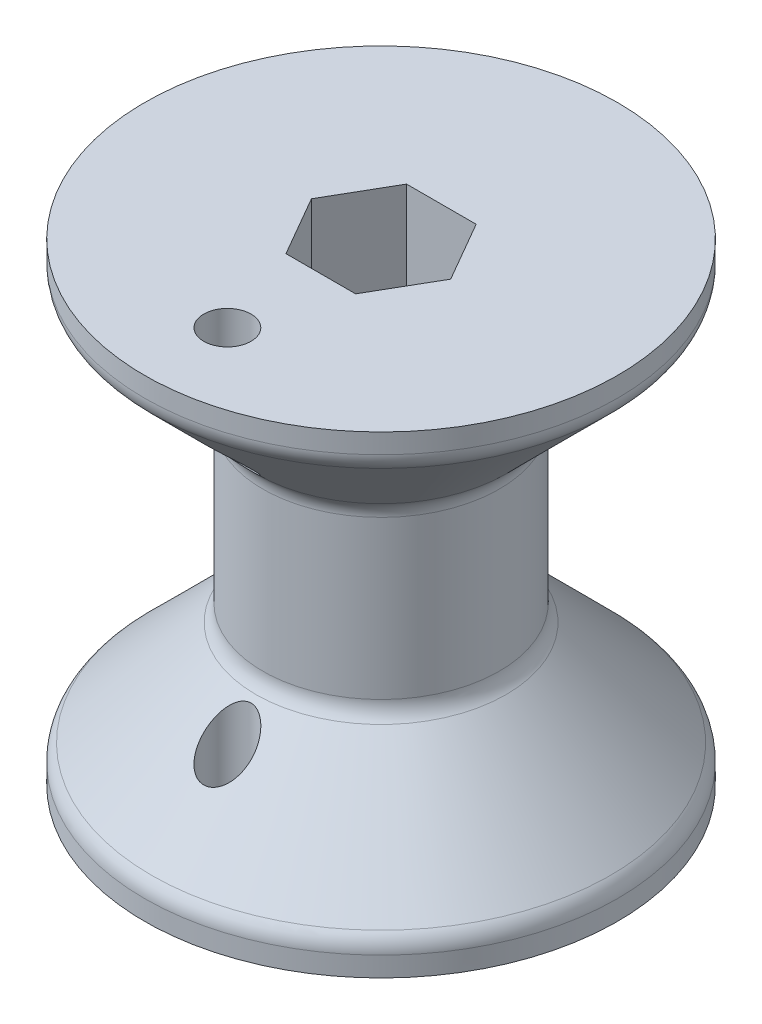
SolidWorks part; units mm, degrees
ref_plane "Front Plane" through (0, 0, 0) normal (0, 0, 1) x (1, 0, 0)
ref_plane "Top Plane" through (0, 0, 0) normal (0, 1, 0) x (1, 0, 0)
ref_plane "Right Plane" through (0, 0, 0) normal (1, 0, 0) x (0, 0, -1)
sketch "Sketch1" plane through (0, 0, 0) normal (1, 0, 0) x (0, 0, -1)
  line L0 (0, 0) -> (0, 25.4)
  line L1 (0, 25.4) -> (25.4, 25.4)
  line L2 (25.4, 25.4) -> (25.4, 22.225)
  line L3 (25.4, 22.225) -> (12.7, 9.525)
  line L4 (12.7, 9.525) -> (12.7, 0)
  line L5 (12.7, 0) -> (0, 0)
  dimension "D1" = 25.4
  dimension "D2" = 45
  dimension "D3" = 3.175
  dimension "D4" = 12.7
  dimension "D5" = 25.4
  dimension "D6" = 9.525
revolve "Revolve1" add sketch "Sketch1" angle 360 about L0
mirror "Mirror1" about plane through (0, 0, -12.7) normal (0, -1, 0) of "Revolve1"
sketch "Sketch2" plane through (0, 25.4, 0) normal (0, 1, 0) x (1, 0, 0)
  line L1 (-7.479, 0) -> (-3.7395, -6.477)
  line L2 (-3.7395, -6.477) -> (3.7395, -6.477)
  line L3 (3.7395, -6.477) -> (7.479, 0)
  line L4 (7.479, 0) -> (3.7395, 6.477)
  line L5 (3.7395, 6.477) -> (-3.7395, 6.477)
  line L6 (-3.7395, 6.477) -> (-7.479, 0)
  circle A0 centre (0, 0) radius 6.477 construction
  circle A1 centre (0, -16.51) radius 2.54
  circle A2 centre (0, 0) radius 25.4 construction
  dimension "D2" = 5.08
  dimension "D1" = 12.954
  dimension "." = 16.51
extrude "Cut-Extrude1" cut sketch "Sketch2" against normal through all
fillet "Fillet1" radius 2.54 4 edges at (0, 22.225, -25.4) (0, -22.225, -25.4) (0, -9.525, -12.7) (0, 9.525, -12.7)
